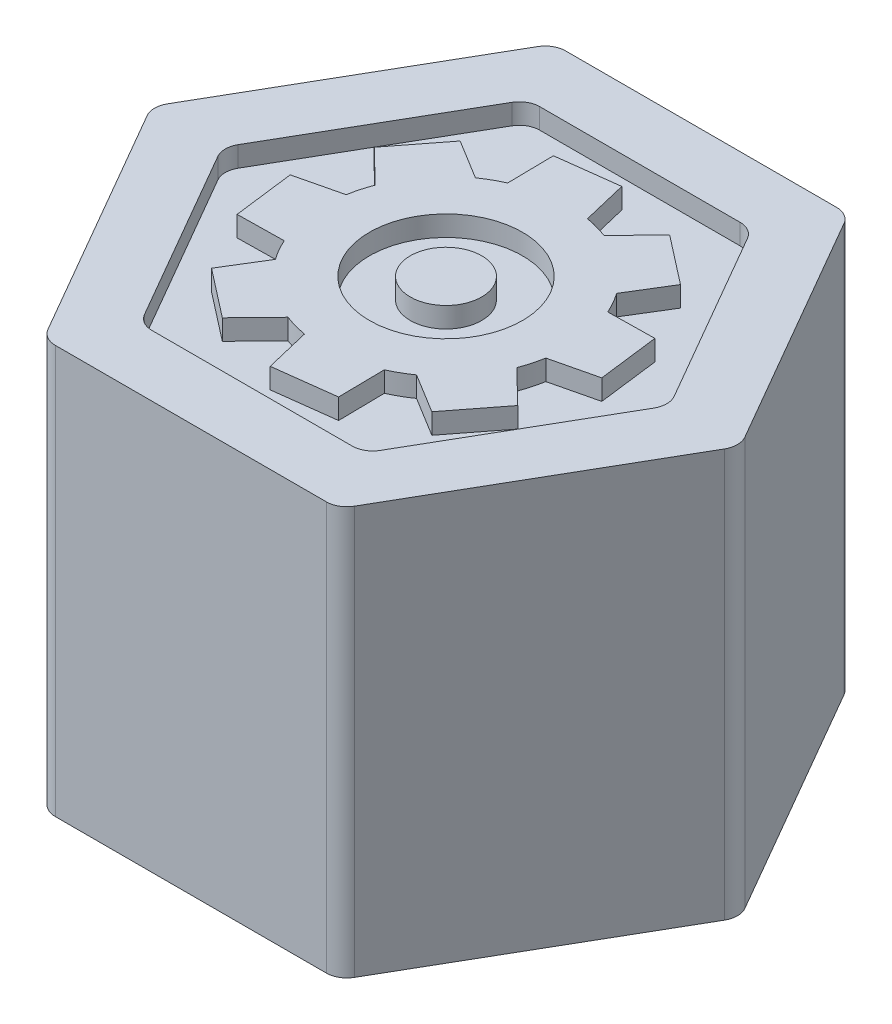
SolidWorks part; units mm, degrees
ref_plane "前视基准面" through (0, 0, 0) normal (0, 0, 1) x (1, 0, 0)
ref_plane "上视基准面" through (0, 0, 0) normal (0, 1, 0) x (1, 0, 0)
ref_plane "右视基准面" through (0, 0, 0) normal (1, 0, 0) x (0, 0, -1)
sketch "草图1" plane through (0, 0, 0) normal (0, 1, 0) x (1, 0, 0)
  line L1 (14.4338, 0) -> (7.2169, 12.5)
  line L2 (7.2169, 12.5) -> (-7.2169, 12.5)
  line L3 (-7.2169, 12.5) -> (-14.4338, 0)
  line L4 (-14.4338, 0) -> (-7.2169, -12.5)
  line L5 (-7.2169, -12.5) -> (7.2169, -12.5)
  line L6 (7.2169, -12.5) -> (14.4338, 0)
  circle A0 centre (0, 0) radius 12.5 construction
  dimension "D1" = 25
extrude "凸台-拉伸1" add sketch "草图1" along normal blind 20
sketch "草图2" plane through (0, 20, 0) normal (0, 1, 0) x (1, 0, 0)
  line L0 (5.4848, -9.5) -> (10.9697, 0)
  line L1 (10.9697, 0) -> (5.4848, 9.5)
  line L2 (5.4848, 9.5) -> (-5.4848, 9.5)
  line L3 (-5.4848, 9.5) -> (-10.9697, 0)
  line L4 (-10.9697, 0) -> (-5.4848, -9.5)
  line L5 (-5.4848, -9.5) -> (5.4848, -9.5)
  line L6 (7.2169, -12.5) -> (14.4338, 0)
  line L7 (14.4338, 0) -> (7.2169, 12.5)
  line L8 (7.2169, 12.5) -> (-7.2169, 12.5)
  line L9 (-7.2169, 12.5) -> (-14.4338, 0)
  line L10 (-14.4338, 0) -> (-7.2169, -12.5)
  line L11 (-7.2169, -12.5) -> (7.2169, -12.5)
  line L12 (7.2169, -12.5) -> (14.4338, 0)
  line L13 (14.4338, 0) -> (7.2169, 12.5)
  line L14 (7.2169, 12.5) -> (-7.2169, 12.5)
  line L15 (-7.2169, 12.5) -> (-14.4338, 0)
  line L16 (-14.4338, 0) -> (-7.2169, -12.5)
  line L17 (-7.2169, -12.5) -> (7.2169, -12.5)
  dimension "D1" = 0
  dimension "D2" = 3
extrude "切除-拉伸1" cut sketch "草图2" against normal blind 1 contours L0 L1 L2 L3 L4 L5
sketch "草图3" plane through (0, 19, 0) normal (0, 1, 0) x (1, 0, 0)
  line L5 (7.7503, 2.4864) -> (5.4759, 2.4524)
  line L6 (7.7503, 2.4864) -> (8.1246, -0.4901)
  line L16 (8.1246, -0.4901) -> (5.9126, -1.0203)
  line L17 (7.9375, 0.9982) -> (5.9531, 0.7486) construction
  line L18 (7.2385, -3.7221) -> (5.6062, -2.138)
  line L19 (7.2385, -3.7221) -> (5.3984, -6.0916)
  line L20 (5.3984, -6.0916) -> (3.4594, -4.9023)
  line L21 (6.3185, -4.9068) -> (4.7388, -3.6801) construction
  line L22 (2.4864, -7.7503) -> (2.4524, -5.4759)
  line L23 (2.4864, -7.7503) -> (-0.4901, -8.1246)
  line L24 (-0.4901, -8.1246) -> (-1.0203, -5.9126)
  line L25 (0.9982, -7.9375) -> (0.7486, -5.9531) construction
  line L26 (-3.7221, -7.2385) -> (-2.138, -5.6062)
  line L27 (-3.7221, -7.2385) -> (-6.0916, -5.3984)
  line L28 (-6.0916, -5.3984) -> (-4.9023, -3.4594)
  line L29 (-4.9068, -6.3185) -> (-3.6801, -4.7388) construction
  line L30 (-7.7503, -2.4864) -> (-5.4759, -2.4524)
  line L31 (-7.7503, -2.4864) -> (-8.1246, 0.4901)
  line L32 (-8.1246, 0.4901) -> (-5.9126, 1.0203)
  line L33 (-7.9375, -0.9982) -> (-5.9531, -0.7486) construction
  line L34 (-7.2385, 3.7221) -> (-5.6062, 2.138)
  line L35 (-7.2385, 3.7221) -> (-5.3984, 6.0916)
  line L36 (-5.3984, 6.0916) -> (-3.4594, 4.9023)
  line L37 (-6.3185, 4.9068) -> (-4.7388, 3.6801) construction
  line L38 (-2.4864, 7.7503) -> (-2.4524, 5.4759)
  line L39 (-2.4864, 7.7503) -> (0.4901, 8.1246)
  line L40 (0.4901, 8.1246) -> (1.0203, 5.9126)
  line L41 (-0.9982, 7.9375) -> (-0.7486, 5.9531) construction
  line L42 (3.7221, 7.2385) -> (2.138, 5.6062)
  line L43 (3.7221, 7.2385) -> (6.0916, 5.3984)
  line L44 (6.0916, 5.3984) -> (4.9023, 3.4594)
  line L45 (4.9068, 6.3185) -> (3.6801, 4.7388) construction
  circle A0 centre (0, 0) radius 6
  circle A2 centre (0, 0) radius 3.75
  circle A3 centre (0, 0) radius 1.75
  point P43 (0, 0)
  dimension "D1" = 12
  dimension "D7" = 3.5
  dimension "D2" = 3
  dimension "D3" = 2
  dimension "D4" = 3.5
  dimension "D6" = 2.25
  dimension "D5" = 8
extrude "凸台-拉伸2" add sketch "草图3" along normal blind 1 contours A0 | A0 L16 L6 L5 | A0 L20 L19 L18 | A0 L24 L23 L22 | A0 L28 L27 L26 | A0 L32 L31 L30 | A0 L36 L35 L34 | A0 L40 L39 L38 | A0 L44 L43 L42 | A3
fillet "圆角1" radius 1 12 edges at (-10.9697, 19.5, 0) (-5.4848, 19.5, 9.5) (5.4848, 19.5, 9.5) (10.9697, 19.5, 0) (5.4848, 19.5, -9.5) (-5.4848, 19.5, -9.5) (-14.4338, 10, 0) (-7.2169, 10, -12.5) (7.2169, 10, -12.5) (14.4338, 10, 0) (7.2169, 10, 12.5) (-7.2169, 10, 12.5)
sketch "草图5" plane through (-10.8253, 0, -6.25) normal (-0.866, 0, -0.5) x (-0.5, 0, 0.866)
  text T0 "5" font "Impact" height in points 48
extrude "切除-拉伸2" cut sketch "草图5" against normal blind 1
